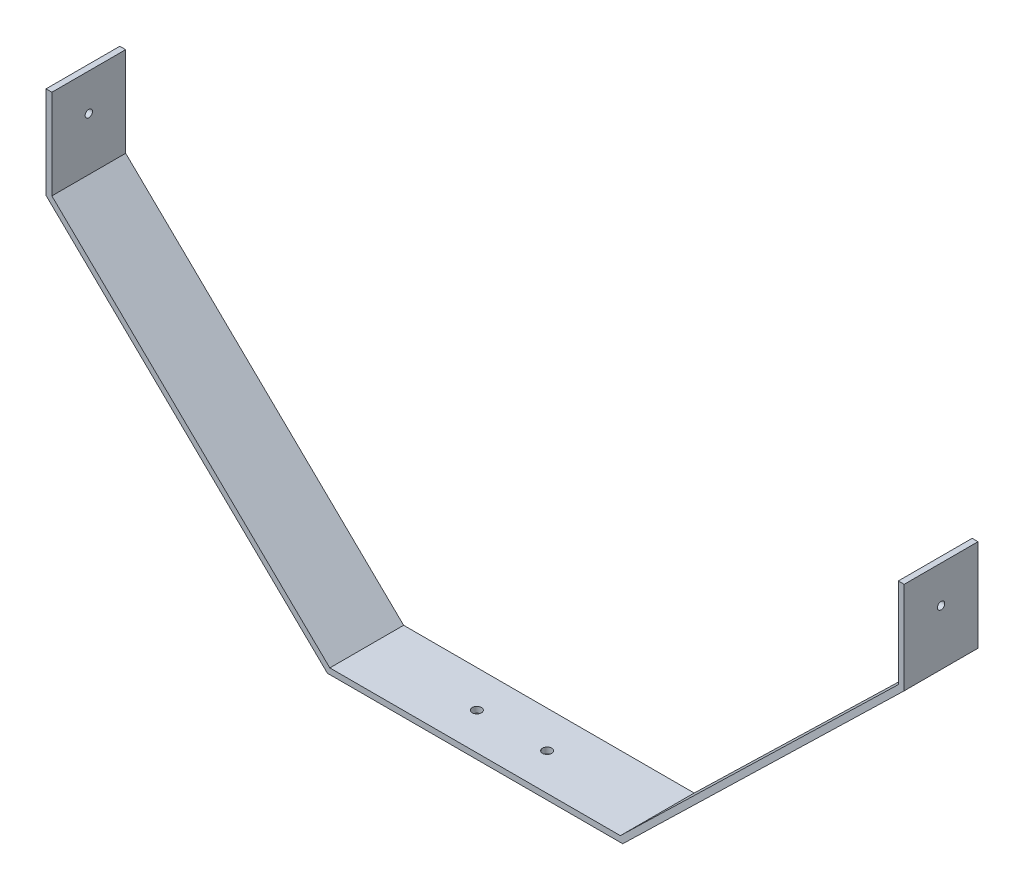
SolidWorks part; units mm, degrees
ref_plane "Front Plane" through (0, 0, 0) normal (0, 0, 1) x (1, 0, 0)
ref_plane "Top Plane" through (0, 0, 0) normal (0, 1, 0) x (1, 0, 0)
ref_plane "Right Plane" through (0, 0, 0) normal (1, 0, 0) x (0, 0, -1)
sketch "Sketch1" plane through (0, 0, 0) normal (0, 0, 1) x (1, 0, 0)
  line L0 (-80, 0) -> (80, 0)
  line L1 (80, 0) -> (232.5, 148)
  line L2 (232.5, 148) -> (232.5, 198)
  line L3 (-80, 0) -> (-232.5, 148)
  line L4 (-232.5, 148) -> (-232.5, 198)
  line L5 (-232.5, 148) -> (232.5, 148) construction
  line L6 (-232.5, 198) -> (232.5, 198) construction
  line L7 (229.325, 149.3431) -> (229.325, 198)
  line L8 (78.7126, 3.175) -> (229.325, 149.3431)
  line L9 (-78.7126, 3.175) -> (78.7126, 3.175)
  line L10 (-78.7126, 3.175) -> (-229.325, 149.3431)
  line L11 (-229.325, 149.3431) -> (-229.325, 198)
  line L12 (-232.5, 198) -> (-229.325, 198)
  line L13 (229.325, 198) -> (232.5, 198)
  point P8 (0, 0)
  dimension "D1" = 160
  dimension "D2" = 465
  dimension "D3" = 198
  dimension "D4" = 50
  dimension "D5" = 3.175
extrude "Boss-Extrude1" add sketch "Sketch1" along normal blind 40
sketch "Sketch3" plane through (0, 3.175, 0) normal (0, 1, 0) x (1, 0, 0)
  line L0 (-78.7126, -20) -> (-19.05, -20) construction
  line L1 (-78.7126, -40) -> (-78.7126, 0) construction
  line L2 (-19.05, -20) -> (19.05, -20) construction
  line L3 (19.05, -20) -> (78.7126, -20) construction
  line L4 (78.7126, -40) -> (78.7126, 0) construction
  circle A0 centre (-19.05, -20) radius 2.5
  circle A1 centre (19.05, -20) radius 2.5
  dimension "D2" = 5
  dimension "D1" = 38.1
extrude "Cut-Extrude1" cut sketch "Sketch3" against normal through all both and the other way through all
sketch "Sketch4" plane through (-232.5, 0, 0) normal (-1, 0, 0) x (0, 0, 1)
  line L0 (20, 198) -> (20, 148) construction
  line L1 (40, 198) -> (0, 198) construction
  line L2 (40, 148) -> (0, 148) construction
  line L3 (0, 178) -> (40, 178) construction
  line L4 (0, 148) -> (0, 198) construction
  line L5 (40, 148) -> (40, 198) construction
  circle A0 centre (20, 178) radius 1.9844
  dimension "D2" = 3.9688
  dimension "D1" = 20
extrude "Cut-Extrude2" cut sketch "Sketch4" against normal through all both
